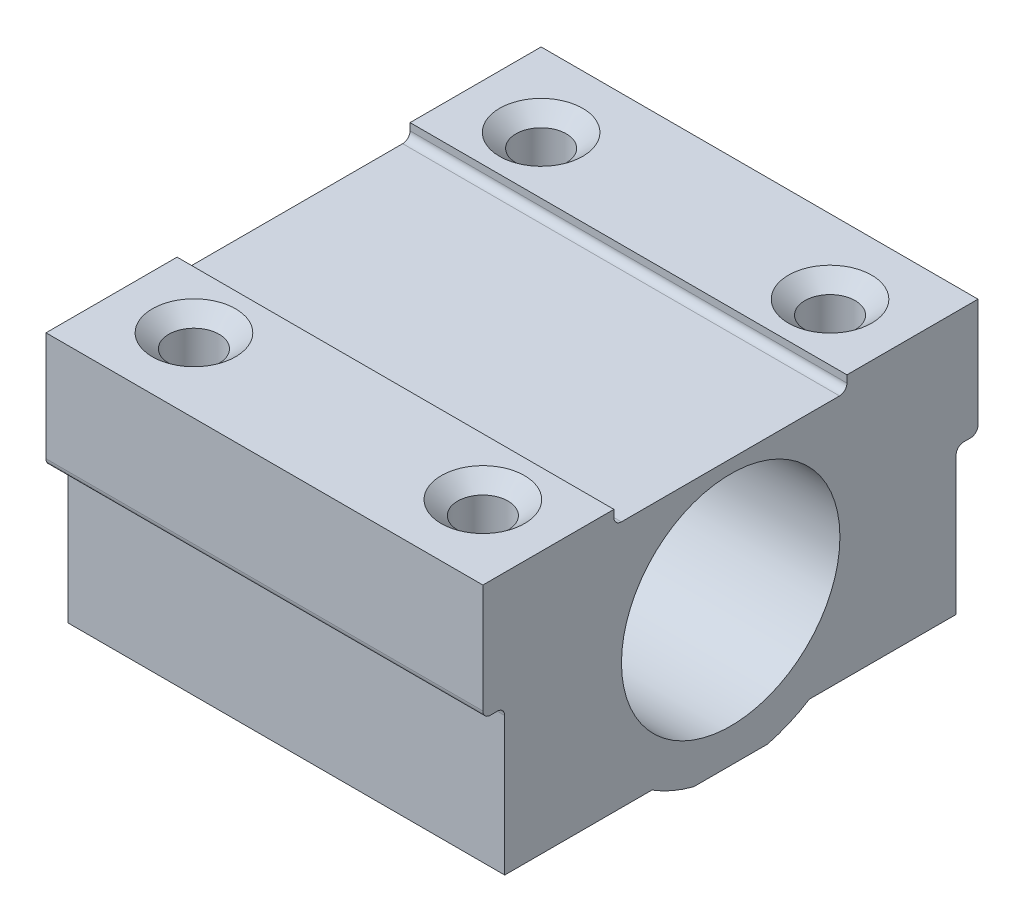
SolidWorks part; units mm, degrees
ref_plane "Front Plane" through (0, 0, 0) normal (0, 0, 1) x (1, 0, 0)
ref_plane "Top Plane" through (0, 0, 0) normal (0, 1, 0) x (1, 0, 0)
ref_plane "Right Plane" through (0, 0, 0) normal (1, 0, 0) x (0, 0, -1)
sketch "Sketch1" plane through (0, 0, 0) normal (1, 0, 0) x (0, 0, -1)
  line L0 (32.5, 0) -> (34, 0)
  line L1 (0, 0) -> (1.5, 0)
  line L2 (0, 0) -> (0, 7.4937)
  line L3 (9, 7) -> (25, 7)
  line L4 (34, 0) -> (34, 7.4937)
  line L6 (1.5, 0) -> (1.5, -10)
  line L7 (1.5, -10) -> (11.6114, -10)
  line L8 (32.5, 0) -> (32.5, -10)
  line L10 (0, 7.4937) -> (0, 8)
  line L11 (0, 8) -> (9, 8)
  line L12 (9, 7) -> (9, 8)
  line L14 (34, 7.4937) -> (34, 8)
  line L15 (34, 8) -> (25, 8)
  line L16 (25, 7) -> (25, 8)
  line L17 (14.4865, -11.2376) -> (19.5495, -11.2376)
  line L18 (22.4246, -10) -> (32.5, -10)
  circle A0 centre (17.018, -1.398) radius 7.5
  arc A1 (11.6114, -10) -> (14.4865, -11.2376) centre (17.018, -1.398) ccw
  arc A2 (19.5495, -11.2376) -> (22.4246, -10) centre (17.018, -1.398) ccw
  point P19 (29.5, 8)
  dimension "D7" = 15
  dimension "D8" = 20.32
  dimension "D1" = 34
  dimension "D2" = 18
  dimension "D3" = 1.5
  dimension "D4" = 10
  dimension "D5" = 1
  dimension "D6" = 9
  dimension "D9" = 9.398
  dimension "D10" = 17.018
extrude "Boss-Extrude1" add sketch "Sketch1" along normal blind 30
hole_wizard "CSK for #4 Flat Head Machine Screw (100)1" positions "Sketch3" profile "Sketch4" countersink size "#4" standard "ANSI Inch"
sketch "Sketch3" plane through (0, 8, 0) normal (0, 1, 0) x (1, 0, 0)
  line L0 (0, 34) -> (0, 25) construction
  line L1 (30, 34) -> (0, 34) construction
  line L2 (30, 0) -> (0, 0) construction
  line L3 (30, 9) -> (30, 0) construction
  point P0 (5.08, 28.92)
  point P2 (24.92, 28.92)
  point P4 (24.92, 5.08)
  point P6 (5.08, 5.08)
  point P13 (0, 0)
  point P16 (0, 0)
  point P17 (0, 0)
  point P18 (0, 0)
  point P19 (0, 0)
  point P20 (0, 0)
  point P21 (0, 0)
  dimension "D1" = 5.08
  dimension "D2" = 5.08
  dimension "D3" = 5.08
  dimension "D4" = 5.08
sketch "Sketch4" plane through (5.08, 8, -28.92) normal (1, 0, 0) x (0, 0, 1)
  line L0 (0, 0) -> (0, 7.3878)
  line L1 (0, 7.3878) -> (1.7272, 6.35)
  line L2 (1.7272, 6.35) -> (1.7272, 0.9484)
  line L3 (1.7272, 0.9484) -> (2.8575, 0)
  line L5 (2.8575, 0) -> (0, 0)
  line L6 (-1.7272, 0.9484) -> (-2.8575, 0) construction
  line L10 (0, 7.3878) -> (-1.7272, 6.35) construction
  line L11 (0, -6.35) -> (0, 107.95) construction
  dimension "Hole Dia." = 3.4544
  dimension "Hole Depth" = 6.35
  dimension "Near C'Sink Dia." = 5.715
  dimension "Near C'Sink Angle" = 100
  dimension "Drill Angle" = 118
fillet "Fillet1" radius 0.508 6 edges at (15, 7, -25) (15, 7, -9) (15, 0, -34) (15, 0, -32.5) (15, 0, 0) (15, 0, -1.5)
